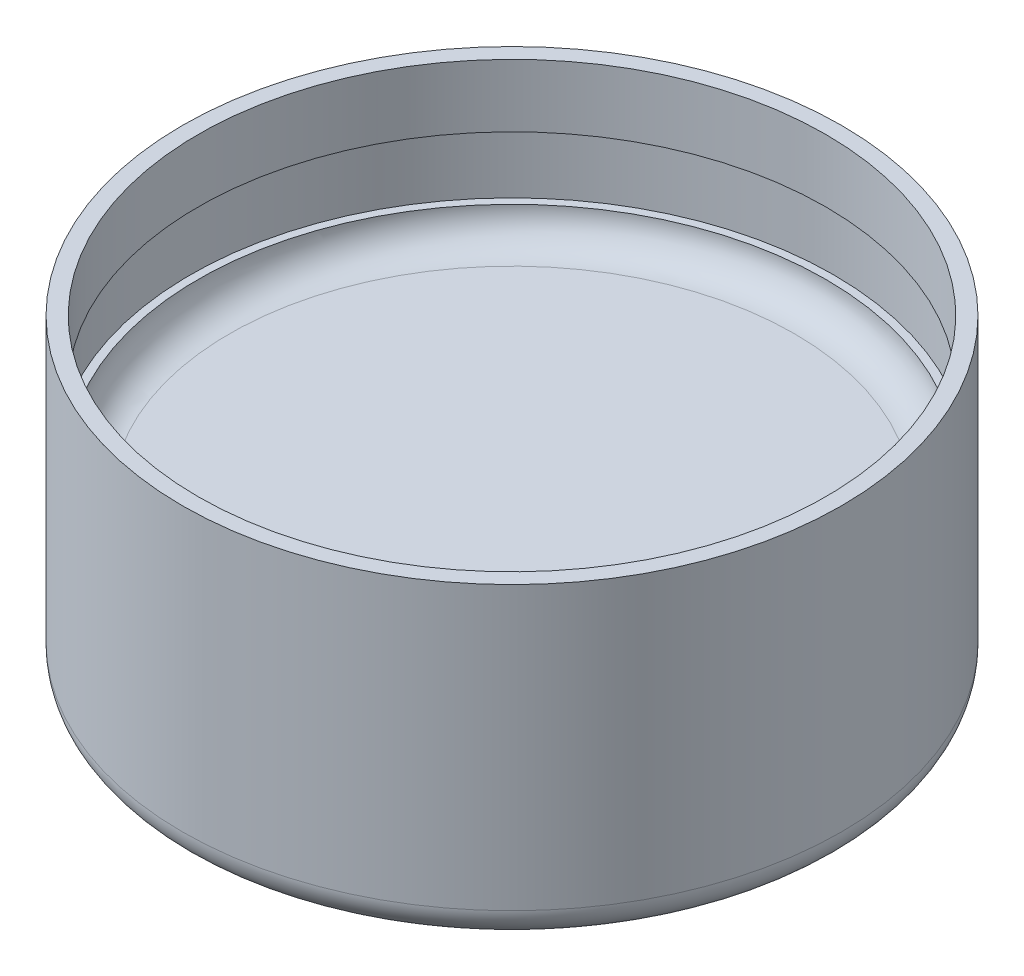
SolidWorks part; units mm, degrees
ref_plane "Front Plane" through (0, 0, 0) normal (0, 0, 1) x (1, 0, 0)
ref_plane "Top Plane" through (0, 0, 0) normal (0, 1, 0) x (1, 0, 0)
ref_plane "Right Plane" through (0, 0, 0) normal (1, 0, 0) x (0, 0, -1)
sketch "Sketch1" plane through (0, 0, 0) normal (0, 1, 0) x (1, 0, 0)
  circle A0 centre (0, 0) radius 105
  dimension "D1" = 210
extrude "Boss-Extrude2" add sketch "Sketch1" along normal blind 100
ref_plane "Plane1" through (0, 100, 0) normal (0, 1, 0) x (1, 0, 0)
sketch "Sketch2" plane through (0, 100, 0) normal (0, 1, 0) x (1, 0, 0)
  circle A0 centre (0, 0) radius 105
  circle A1 centre (0, 0) radius 100
  dimension "D1" = 200
extrude "Cut-Extrude2" cut sketch "Sketch2" against normal blind 50 contours A1
fillet "Fillet1" radius 10 1 edges at (0, 50, 100)
fillet "Fillet2" radius 10 1 edges at (0, 0, 105)
ref_plane "Plane2" through (0, 50, 0) normal (0, 1, 0) x (1, 0, 0)
sketch "Sketch4" plane through (0, 0, 0) normal (0, 0, 1) x (1, 0, 0)
  line L0 (0, 0) -> (0, 50)
  line L1 (115.5, 50) -> (-115.5, 50) construction
  line L3 (0, 63) -> (0, 60)
  line L4 (0, 60) -> (102.5, 60)
  line L5 (0, 60) -> (0, 80)
  line L6 (0, 80) -> (102.5, 80)
  line L7 (102.5, 60) -> (102.5, 80)
  dimension "D1" = 13
  dimension "D2" = 3
  dimension "D3" = 20
  dimension "D4" = 102.5
revolve "Cut-Revolve1" cut sketch "Sketch4" angle 360 about L0
